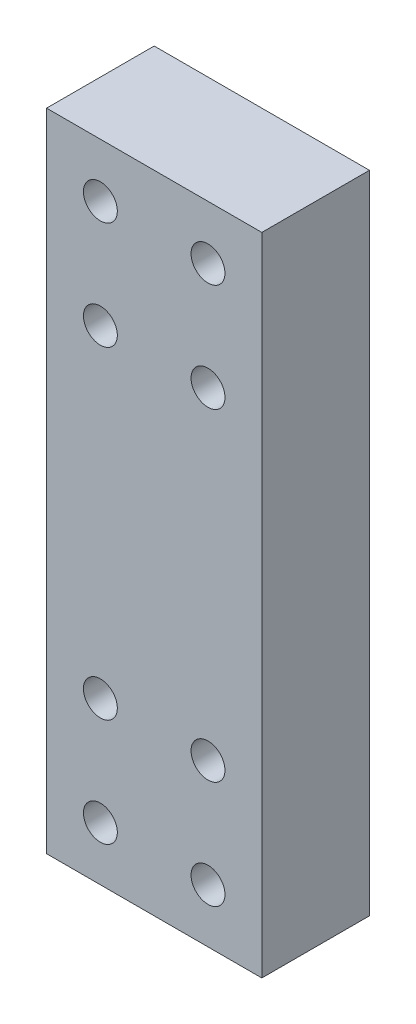
SolidWorks part; units mm, degrees
ref_plane "前视基准面" through (0, 0, 0) normal (0, 0, 1) x (1, 0, 0)
ref_plane "上视基准面" through (0, 0, 0) normal (0, 1, 0) x (1, 0, 0)
ref_plane "右视基准面" through (0, 0, 0) normal (1, 0, 0) x (0, 0, -1)
other "Configuration Table"
sketch "草图1" plane through (0, 0, 0) normal (0, 0, 1) x (1, 0, 0)
  line L1 (0, 0) -> (20, 0)
  line L2 (0, 0) -> (0, -60)
  line L3 (0, -60) -> (20, -60)
  line L4 (20, 0) -> (20, -60)
  dimension "D1" = 20
  dimension "D2" = 60
extrude "凸台-拉伸1" add sketch "草图1" along normal blind 10
sketch "草图2" plane through (0, 0, 10) normal (0, 0, 1) x (1, 0, 0)
  line L0 (0, -30) -> (20, -30) construction
  line L1 (0, 0) -> (0, -60) construction
  line L2 (20, -60) -> (20, 0) construction
  line L3 (0, -10) -> (20, -10) construction
  line L4 (10, 0) -> (10, -10) construction
  line L5 (20, 0) -> (0, 0) construction
  line L6 (10, -60) -> (10, -50) construction
  line L7 (0, -50) -> (20, -50) construction
  circle A0 centre (5, -5) radius 1.575
  circle A1 centre (15, -5) radius 1.575
  circle A2 centre (15, -15) radius 1.575
  circle A3 centre (5, -15) radius 1.575
  circle A4 centre (5, -45) radius 1.575
  circle A5 centre (15, -45) radius 1.575
  circle A6 centre (15, -55) radius 1.575
  circle A7 centre (5, -55) radius 1.575
  dimension "D1" = 3.15
  dimension "D2" = 5
  dimension "D3" = 5
  dimension "D4" = 10
extrude "切除-拉伸1" cut sketch "草图2" against normal through all
